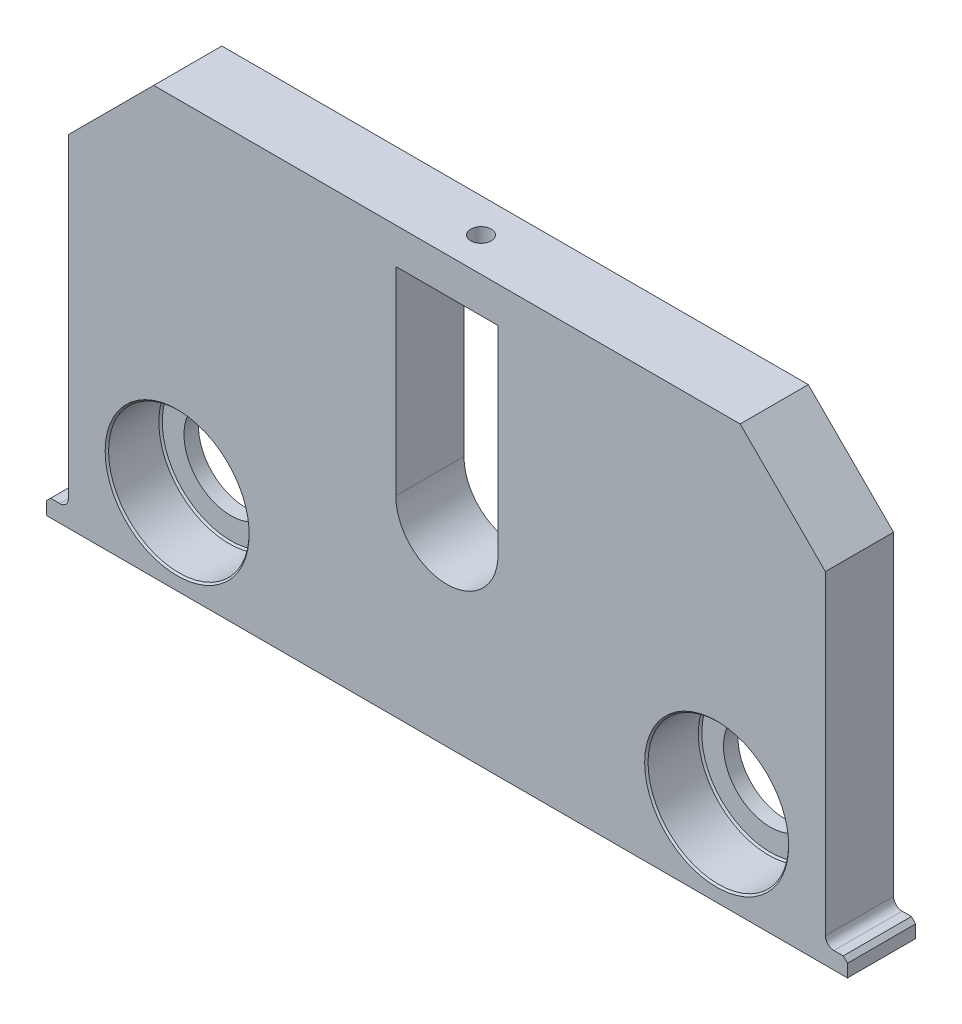
SolidWorks part; units mm, degrees
ref_plane "Front Plane" through (0, 0, 0) normal (0, 0, 1) x (1, 0, 0)
ref_plane "Top Plane" through (0, 0, 0) normal (0, 1, 0) x (1, 0, 0)
ref_plane "Right Plane" through (0, 0, 0) normal (1, 0, 0) x (0, 0, -1)
sketch "Sketch1" plane through (0, 0, 0) normal (0, 0, 1) x (1, 0, 0)
  line L0 (-445, 0) -> (445, 0)
  line L1 (-444.0633, 20) -> (-444.0633, 399.9991)
  line L2 (-344.0633, 499.9991) -> (344.0633, 499.9991)
  line L3 (444.0633, 399.9991) -> (444.0633, 20)
  line L4 (-444.0633, 399.9991) -> (-344.0633, 499.9991)
  line L5 (344.0633, 499.9991) -> (444.0633, 399.9991)
  line L6 (0, 0) -> (0, 646.835) construction
  line L7 (0, 0) -> (50000, 0) construction
  line L8 (445, 0) -> (470, 0)
  line L9 (470, 0) -> (470, 15)
  line L10 (465, 20) -> (444.0633, 20)
  line L11 (470, 15) -> (465, 20)
  line L12 (-445, 0) -> (-470, 0)
  line L13 (-470, 0) -> (-470, 15)
  line L14 (-465, 20) -> (-444.0633, 20)
  line L15 (-470, 15) -> (-465, 20)
  line L16 (-316.5, 225) -> (316.5, 225) construction
  line L17 (-60, 457.9991) -> (60, 457.9991)
  line L18 (-316.5, 235) -> (316.5, 235) construction
  line L19 (-60, 457.9991) -> (-60, 225)
  line L20 (60, 457.9991) -> (60, 225)
  circle A0 centre (-316.5, 100) radius 55
  circle A1 centre (-316.5, 100) radius 125 construction
  circle A2 centre (316.5, 100) radius 125 construction
  circle A3 centre (316.5, 100) radius 55
  arc A4 (-60, 225) -> (60, 225) centre (0, 225) ccw
  point P4 (0, 0)
  point P6 (-444.0633, 499.9991)
  point P7 (444.0633, 499.9991)
  point P22 (470, 20)
  point P30 (-470, 20)
  point P35 (0, 457.9991)
  point P39 (0, 0)
  dimension "D3" = 250
  dimension "D4" = 110
  dimension "D14" = 232.9991
  dimension "D1" = 500
  dimension "D2" = 890
  dimension "D5" = 633
  dimension "D8" = 20
  dimension "D9" = 470
  dimension "D10" = 100
  dimension "D11" = 120
  dimension "D15" = 42
  dimension "D13" = 10
extrude "Boss-Extrude1" add sketch "Sketch1" along normal mid plane 80
fillet "Fillet1" radius 10 2 edges at (444.0633, 20, 0) (-444.0633, 20, 0)
sketch "Sketch2" plane through (0, 457.9991, 0) normal (0, -1, 0) x (1, 0, 0)
  circle A0 centre (0, 0) radius 12
  dimension "D1" = 24
extrude "Cut-Extrude1" cut sketch "Sketch2" against normal through all
sketch "Sketch3" plane through (0, 0, 40) normal (0, 0, 1) x (1, 0, 0)
  circle A0 centre (-316.5, 100) radius 82.5
  circle A1 centre (316.5, 100) radius 82.5
  circle A2 centre (-316.5, 100) radius 55 construction
  circle A3 centre (-316.5, 100) radius 55
  circle A4 centre (316.5, 100) radius 55 construction
  circle A5 centre (316.5, 100) radius 55
  dimension "D1" = 165
extrude "Cut-Extrude2" cut sketch "Sketch3" against normal blind 63
chamfer "Chamfer1" distance 2 angle 45 4 edges at (399, 100, -23) (399, 100, 40) (-234, 100, -23) (-234, 100, 40)
